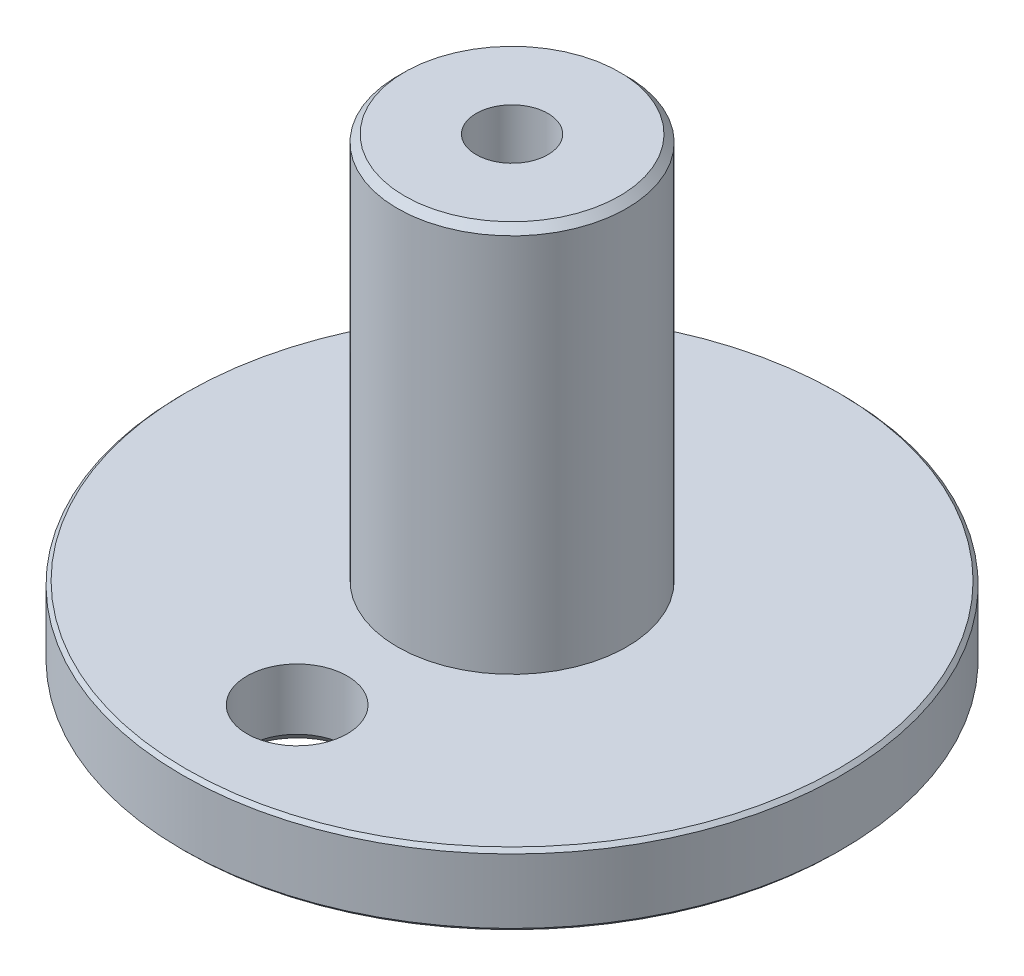
SolidWorks part; units mm, degrees
ref_plane "Front Plane" through (0, 0, 0) normal (0, 0, 1) x (1, 0, 0)
ref_plane "Top Plane" through (0, 0, 0) normal (0, 1, 0) x (1, 0, 0)
ref_plane "Right Plane" through (0, 0, 0) normal (1, 0, 0) x (0, 0, -1)
sketch "Sketch1" plane through (0, 0, 0) normal (0, 1, 0) x (1, 0, 0)
  circle A0 centre (0, 0) radius 23
  dimension "D1" = 46
extrude "Boss-Extrude1" add sketch "Sketch1" along normal blind 32
sketch "Sketch2" plane through (0, 32, 0) normal (0, 1, 0) x (1, 0, 0)
  circle A0 centre (0, 0) radius 8
  dimension "D1" = 16
extrude "Cut-Extrude1" cut sketch "Sketch2" against normal blind 27 flip side to cut
sketch "Sketch3" plane through (0, 32, 0) normal (0, 1, 0) x (1, 0, 0)
  circle A0 centre (0, 0) radius 2.5
  dimension "D1" = 5
extrude "Cut-Extrude2" cut sketch "Sketch3" against normal through all
chamfer "Chamfer1" distance 0.5 angle 45 1 edges at (0, 32, 8)
chamfer "Chamfer2" distance 0.25 angle 45 2 edges at (0, 0, 23) (0, 5, 23)
sketch "Sketch4" plane through (0, 0, 0) normal (0, -1, 0) x (1, 0, 0)
  circle A0 centre (0, 15) radius 3.5
  dimension "D2" = 7
  dimension "D1" = 15
extrude "Cut-Extrude3" cut sketch "Sketch4" against normal through all
chamfer "Chamfer3" distance 0.75 angle 45 1 edges at (0, 0, 11.5)
